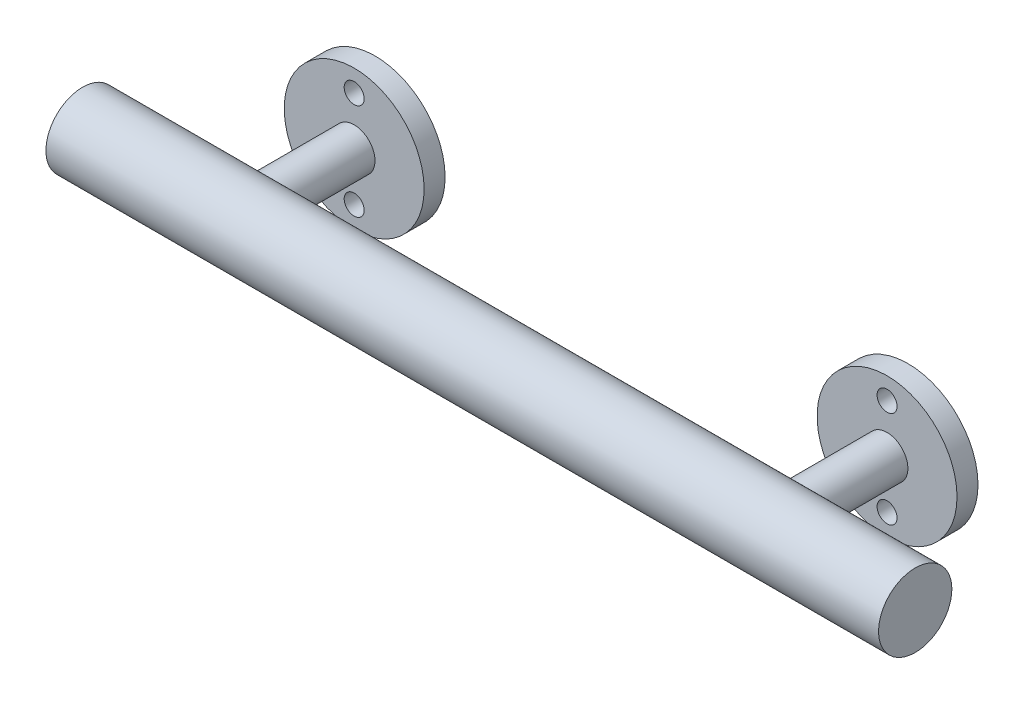
SolidWorks part; units mm, degrees
ref_plane "前基準面" through (0, 0, 0) normal (0, 0, 1) x (1, 0, 0)
ref_plane "上基準面" through (0, 0, 0) normal (0, 1, 0) x (1, 0, 0)
ref_plane "右基準面" through (0, 0, 0) normal (1, 0, 0) x (0, 0, -1)
sketch "草圖1" plane through (0, 0, 0) normal (0, 0, 1) x (1, 0, 0)
  line L0 (-43.2026, 0) -> (74.7974, 0) construction
  circle A0 centre (-64.2026, 0) radius 21
  circle A1 centre (95.7974, 0) radius 21
  dimension "D1" = 42
  dimension "D2" = 42
  dimension "D3" = 118
extrude "填料-伸長3" add sketch "草圖1" along normal blind 6.3
sketch "草圖3" plane through (0, 0, 0) normal (0, 0, 1) x (1, 0, 0)
  circle A0 centre (-64.2026, 0) radius 6.25
  circle A1 centre (95.7974, 0) radius 6.25
  dimension "D1" = 12.5
  dimension "D2" = 12.5
extrude "填料-伸長4" add sketch "草圖3" along normal blind 33
sketch "草圖4" plane through (0, 0, 0) normal (1, 0, 0) x (0, 0, -1)
  circle A0 centre (-42.0519, 0) radius 11
  dimension "D1" = 22
extrude "填料-伸長5" add sketch "草圖4" along normal blind 140 and the other way blind 110
sketch "草圖5" plane through (0, 0, 6.3) normal (0, 0, 1) x (1, 0, 0)
  line L0 (-64.2026, 21) -> (-64.2026, 14.5) construction
  line L1 (-64.2026, -21) -> (-64.2026, -14.5) construction
  line L2 (95.7974, 21) -> (95.7974, 14.5) construction
  line L3 (95.7974, -21) -> (95.7974, -14.5)
  circle A0 centre (-64.2026, 0) radius 21 construction
  circle A1 centre (-64.2026, 14.5) radius 3
  circle A2 centre (-64.2026, -14.5) radius 3
  circle A3 centre (95.7974, 0) radius 21 construction
  circle A4 centre (95.7974, 14.5) radius 3
  circle A5 centre (95.7974, -14.5) radius 3
  dimension "D2" = 6
  dimension "D4" = 6
  dimension "D6" = 6
  dimension "D8" = 6
  dimension "D1" = 6.5
  dimension "D3" = 6.5
  dimension "D5" = 6.5
  dimension "D7" = 6.5
extrude "除料-伸長1" cut sketch "草圖5" against normal blind 10 contours A1 | A2 | A4 | A5
